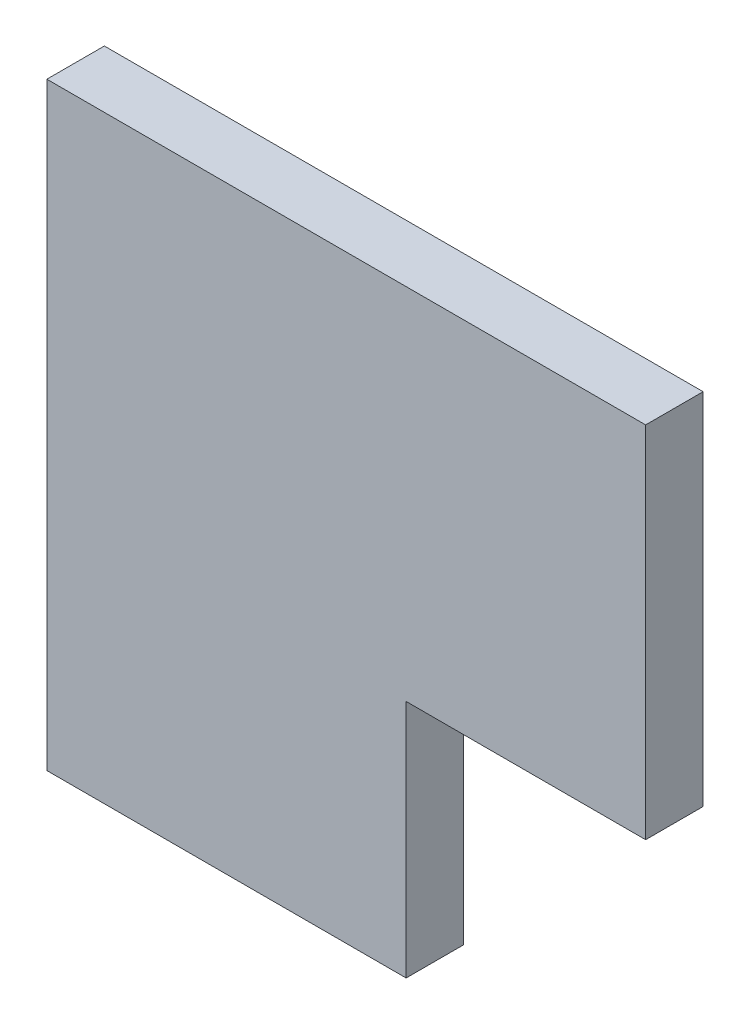
SolidWorks part; units mm, degrees
material "PBT General Purpose"
ref_plane "Front Plane" through (0, 0, 0) normal (0, 0, 1) x (1, 0, 0)
ref_plane "Top Plane" through (0, 0, 0) normal (0, 1, 0) x (1, 0, 0)
ref_plane "Right Plane" through (0, 0, 0) normal (1, 0, 0) x (0, 0, -1)
sketch "Sketch1" plane through (0, 0, 0) normal (0, 0, 1) x (1, 0, 0)
  line L0 (0, 0) -> (0, 1.5)
  line L1 (0, 1.5) -> (-2.5, 1.5)
  line L2 (-2.5, 1.5) -> (-2.5, -1)
  line L3 (-2.5, -1) -> (-1, -1)
  line L4 (-1, -1) -> (-1, 0)
  line L5 (-1, 0) -> (0, 0)
  dimension "D1" = 1.5
  dimension "D2" = 1
  dimension "D3" = 1
  dimension "D4" = 1.5
extrude "Boss-Extrude1" add sketch "Sketch1" along normal mid plane 0.24
